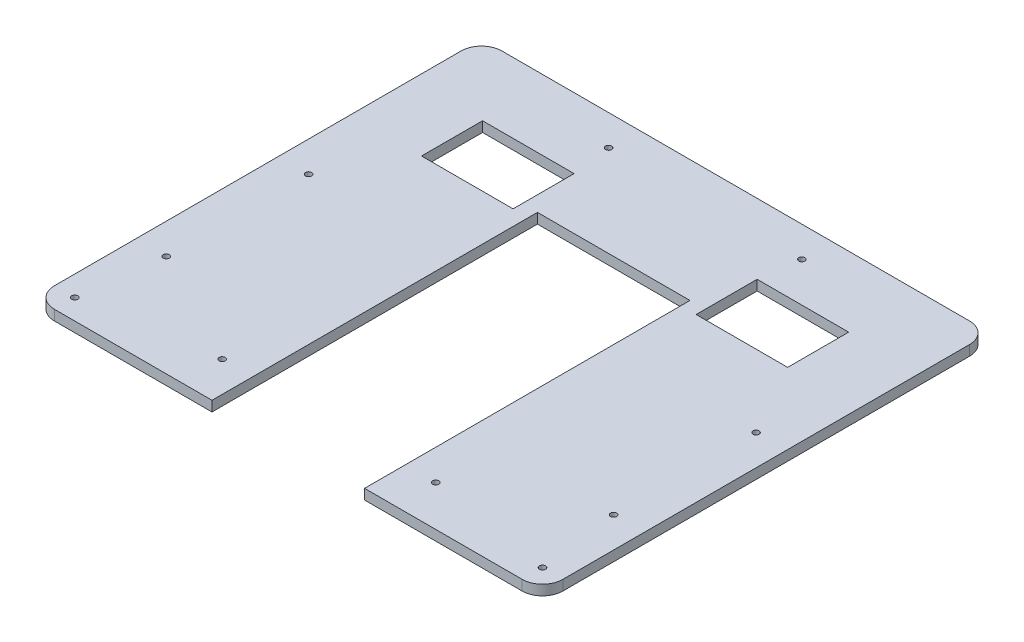
SolidWorks part; units mm, degrees
ref_plane "前视基准面" through (0, 0, 0) normal (0, 0, 1) x (1, 0, 0)
ref_plane "上视基准面" through (0, 0, 0) normal (0, 1, 0) x (1, 0, 0)
ref_plane "右视基准面" through (0, 0, 0) normal (1, 0, 0) x (0, 0, -1)
sketch "草图1" plane through (0, 0, 0) normal (0, 1, 0) x (1, 0, 0)
  line L1 (10, 0) -> (240, 0)
  line L2 (0, -10) -> (0, -210)
  line L3 (10, -220) -> (240, -220)
  line L4 (250, -10) -> (250, -210)
  arc A0 (0, -210) -> (10, -220) centre (10, -210) ccw
  arc A1 (240, -220) -> (250, -210) centre (240, -210) ccw
  arc A2 (240, 0) -> (250, -10) centre (240, -10) cw
  arc A3 (10, 0) -> (0, -10) centre (10, -10) ccw
  point P9 (250, -220)
  point P12 (250, 0)
  point P15 (0, 0)
  dimension "D3" = 10
  dimension "D1" = 250
  dimension "D2" = 220
extrude "凸台-拉伸1" add sketch "草图1" along normal blind 5
sketch "草图2" plane through (0, 0, 0) normal (0, -1, 0) x (1, 0, 0)
  line L0 (239.1778, 11.85) -> (239.1778, 76.15) construction
  line L1 (239.1778, 11.85) -> (239.1778, 76.15)
  line L2 (250, 210) -> (250, 10) construction
  line L3 (239.1778, 76.15) -> (250, 76.15)
  line L4 (239.1778, 76.15) -> (239.1778, 0)
  line L5 (239.1778, 0) -> (250, 0)
  line L6 (250, 76.15) -> (250, 0)
  line L7 (125, 220) -> (125, 0) construction
  line L8 (10, 220) -> (240, 220) construction
  line L9 (240, 0) -> (10, 0) construction
  line L10 (0, 76.15) -> (0, 0)
  line L11 (10.8222, 0) -> (0, 0)
  line L12 (10.8222, 76.15) -> (10.8222, 0)
  line L13 (10.8222, 76.15) -> (0, 76.15)
sketch "草图4" plane through (0, 0, 0) normal (0, -1, 0) x (1, 0, 0)
  line L1 (125, 0) -> (125, 220) construction
  line L2 (240, 0) -> (10, 0) construction
  line L3 (10, 220) -> (240, 220) construction
  line L8 (170, 64.475) -> (170, 34.475)
  line L16 (215, 34.475) -> (170, 34.475)
  line L17 (215, 64.475) -> (215, 34.475)
  line L18 (215, 64.475) -> (170, 64.475)
  line L19 (209.9, 64.475) -> (215, 64.475)
  line L20 (215, 64.475) -> (215, 46.825)
  line L21 (204.1, 64.475) -> (199, 64.475)
  line L22 (209.9, 64.475) -> (215, 64.475)
  line L23 (204.1, 64.475) -> (199, 64.475)
  line L24 (40.1, 64.475) -> (45.9, 64.475)
  line L25 (35, 64.475) -> (35, 46.825)
  line L26 (45.9, 64.475) -> (51, 64.475)
  line L27 (215, 64.475) -> (215, 46.825)
  line L28 (209.9, 64.475) -> (204.1, 64.475)
  line L29 (0, 10) -> (0, 210) construction
  line L30 (40.1, 64.475) -> (35, 64.475)
  line L31 (45.9, 64.475) -> (51, 64.475)
  line L33 (35, 64.475) -> (35, 46.825)
  line L35 (40.1, 64.475) -> (35, 64.475)
  line L38 (35, 64.475) -> (80, 64.475)
  line L39 (35, 64.475) -> (35, 34.475)
  line L120 (35, 34.475) -> (80, 34.475)
  line L121 (80, 64.475) -> (80, 34.475)
  dimension "D3" = 45
  dimension "D4" = 30
  dimension "D1" = 35
extrude "切除-拉伸3" cut sketch "草图4" against normal blind 5
sketch "草图5" plane through (0, 0, 0) normal (0, -1, 0) x (1, 0, 0)
  line L0 (125, 220) -> (125, 0) construction
  line L1 (10, 220) -> (240, 220) construction
  line L2 (240, 0) -> (10, 0) construction
  line L3 (87.5, 220) -> (162.5, 220) construction
  line L4 (87.5, 220) -> (87.5, 60)
  line L5 (162.5, 220) -> (87.5, 220)
  line L6 (162.5, 220) -> (162.5, 60)
  line L7 (162.5, 60) -> (87.5, 60)
  point P11 (125, 60)
  dimension "D1" = 37.5
  dimension "D2" = 160
extrude "切除-拉伸4" cut sketch "草图5" against normal blind 5
sketch "草图6" plane through (0, 0, 0) normal (0, -1, 0) x (1, 0, 0)
  line L0 (72.5, 220) -> (72.5, 200) construction
  line L1 (10, 220) -> (87.5, 220) construction
  line L2 (72.5, 200) -> (87.5, 200) construction
  line L7 (87.5, 220) -> (87.5, 60) construction
  line L8 (125, 60) -> (125, 181.8158) construction
  line L9 (87.5, 60) -> (162.5, 60) construction
  line L10 (87.5, 60) -> (87.5, 0) construction
  line L11 (240, 0) -> (10, 0) construction
  line L12 (87.5, 20) -> (92.5, 20) construction
  line L13 (92.5, 20) -> (92.5, 0) construction
  line L14 (92.5, 20) -> (107.5, 20) construction
  circle A0 centre (72.5, 200) radius 1.5
  circle A3 centre (177.5, 200) radius 1.5
  dimension "D3" = 3
  dimension "D1" = 20
  dimension "D2" = 15
  dimension "D4" = 5
  dimension "D5" = 20
  dimension "D6" = 15
extrude "切除-拉伸5" cut sketch "草图6" against normal up to next
sketch "草图7" plane through (0, 0, 0) normal (0, -1, 0) x (1, 0, 0)
  line L0 (17, 15) -> (17, 73) construction
  line L1 (25, 29) -> (25, 59) construction
  line L2 (17, 44) -> (25, 44) construction
  line L3 (240, 0) -> (10, 0) construction
  line L5 (125, 60) -> (125, 0) construction
  line L6 (87.5, 60) -> (162.5, 60) construction
  line L8 (233, 44) -> (225, 44) construction
  line L9 (225, 29) -> (225, 59) construction
  line L10 (233, 15) -> (233, 73) construction
  line L11 (0, 10) -> (0, 210) construction
  circle A0 centre (17, 15) radius 1.6
  circle A1 centre (25, 29) radius 1.6
  circle A2 centre (25, 59) radius 1.6
  circle A3 centre (17, 73) radius 1.6
  circle A4 centre (233, 73) radius 1.6
  circle A5 centre (225, 59) radius 1.6
  circle A6 centre (225, 29) radius 1.6
  circle A7 centre (233, 15) radius 1.6
  dimension "D1" = 8
  dimension "D2" = 58
  dimension "D3" = 30
  dimension "D4" = 58
  dimension "D5" = 17
  dimension "D6" = 15
sketch "草图8" plane through (0, 0, 0) normal (0, -1, 0) x (1, 0, 0)
  line L0 (250, 170) -> (235, 170) construction
  line L1 (250, 210) -> (250, 10) construction
  line L2 (235, 170) -> (235, 220) construction
  line L3 (162.5, 220) -> (240, 220) construction
  line L4 (235, 170) -> (235, 100) construction
  line L5 (235, 100) -> (250, 100) construction
  line L6 (125, 60) -> (125, 122.441) construction
  line L7 (87.5, 60) -> (162.5, 60) construction
  line L8 (15, 170) -> (15, 100) construction
  circle A0 centre (235, 170) radius 1.5
  circle A1 centre (235, 100) radius 1.5
  circle A2 centre (15, 100) radius 1.5
  circle A3 centre (15, 170) radius 1.5
  dimension "D4" = 3
  dimension "D5" = 3
  dimension "D1" = 15
  dimension "D2" = 50
  dimension "D3" = 70
extrude "切除-拉伸8" cut sketch "草图8" against normal up to next
sketch "草图9" plane through (0, 0, 0) normal (0, -1, 0) x (1, 0, 0)
  line L0 (87.5, 60) -> (87.5, 0) construction
  line L1 (240, 0) -> (10, 0) construction
  line L2 (87.5, 0) -> (87.5, 15) construction
  line L3 (87.5, 15) -> (77.5, 15) construction
  line L4 (10, 220) -> (10, 210) construction
  line L5 (125, 60) -> (125, 0) construction
  line L6 (87.5, 60) -> (162.5, 60) construction
  circle A0 centre (77.5, 15) radius 1.5
  circle A1 centre (10, 210) radius 1.5
  circle A2 centre (240, 210) radius 1.5
  circle A3 centre (172.5, 15) radius 1.5
  dimension "D3" = 3
  dimension "D4" = 3
  dimension "D1" = 15
  dimension "D2" = 10
extrude "切除-拉伸9" cut sketch "草图9" against normal up to next
sketch "草图10" plane through (0, 0, 0) normal (0, -1, 0) x (1, 0, 0)
  line L0 (125, 60) -> (125, 0) construction
  line L1 (0, 0) -> (8, 0)
  line L2 (0, 0) -> (0, 85)
  line L3 (0, 85) -> (8, 85)
  line L4 (8, 0) -> (8, 85)
  line L5 (87.5, 60) -> (162.5, 60) construction
  line L6 (240, 0) -> (10, 0) construction
  line L7 (242, 0) -> (242, 85)
  line L8 (250, 85) -> (242, 85)
  line L9 (250, 0) -> (250, 85)
  line L10 (250, 0) -> (242, 0)
  dimension "D1" = 8
  dimension "D2" = 85
